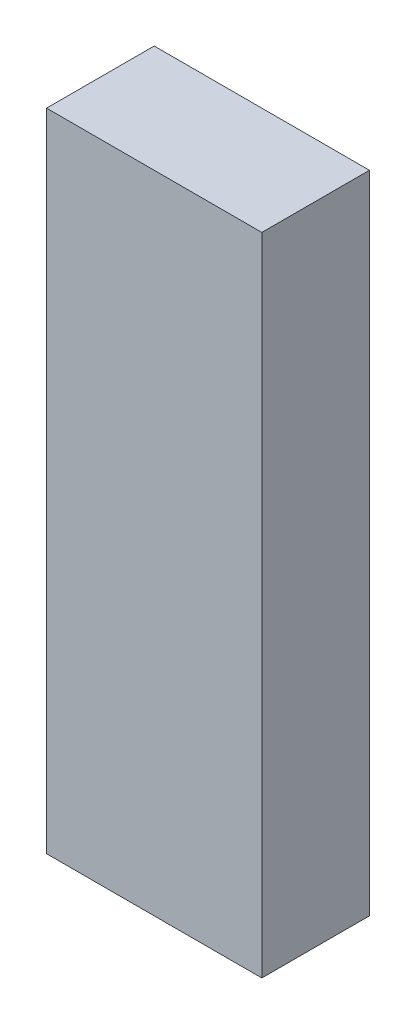
SolidWorks part; units mm, degrees
ref_plane "Front Plane" through (0, 0, 0) normal (0, 0, 1) x (1, 0, 0)
ref_plane "Top Plane" through (0, 0, 0) normal (0, 1, 0) x (1, 0, 0)
ref_plane "Right Plane" through (0, 0, 0) normal (1, 0, 0) x (0, 0, -1)
sketch "Sketch1" plane through (0, 0, 0) normal (0, 1, 0) x (1, 0, 0)
  line L1 (-59.3141, 37.2509) -> (42.2859, 37.2509)
  line L2 (-59.3141, 37.2509) -> (-59.3141, -13.5491)
  line L3 (-59.3141, -13.5491) -> (42.2859, -13.5491)
  line L4 (42.2859, 37.2509) -> (42.2859, -13.5491)
  dimension "D1" = 101.6
  dimension "D2" = 50.8
extrude "Boss-Extrude1" add sketch "Sketch1" along normal blind 304.8
